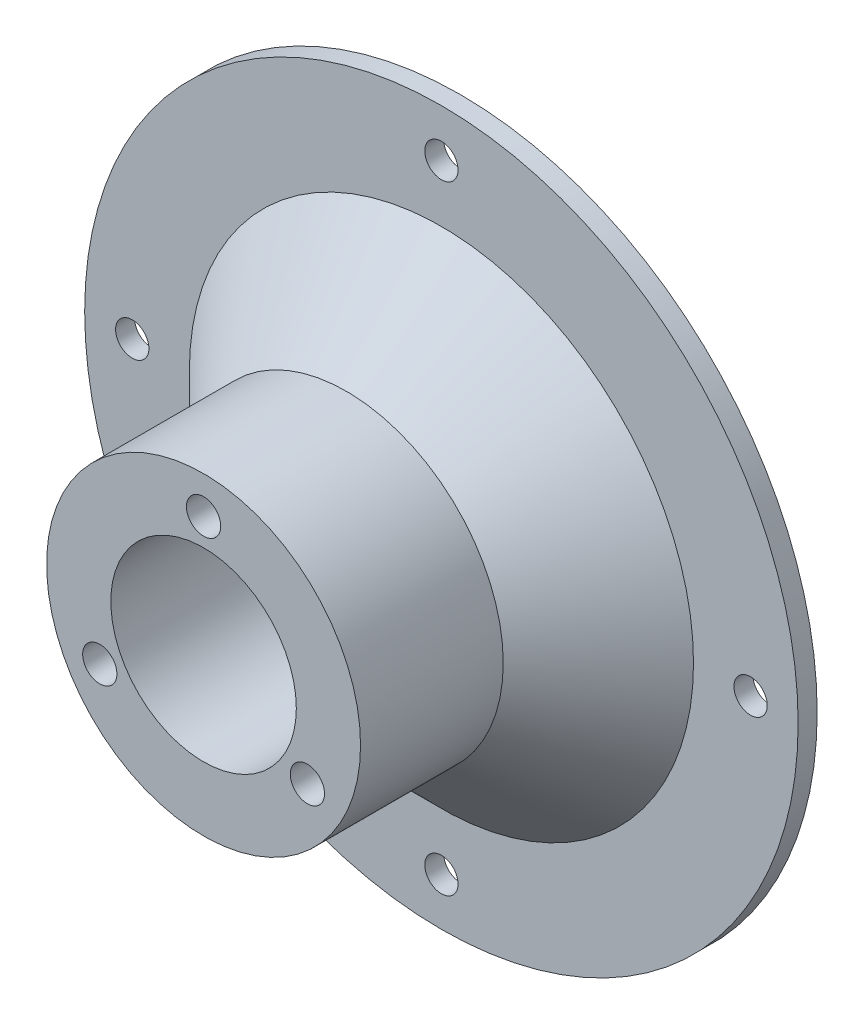
SolidWorks part; units mm, degrees
ref_plane "Спереди" through (0, 0, 0) normal (0, 0, 1) x (1, 0, 0)
ref_plane "Сверху" through (0, 0, 0) normal (0, 1, 0) x (1, 0, 0)
ref_plane "Справа" through (0, 0, 0) normal (1, 0, 0) x (0, 0, -1)
other "Configuration Table"
sketch "Эскиз1" plane through (0, 0, 0) normal (0, 0, 1) x (1, 0, 0)
  circle A0 centre (0, 0) radius 37.5
  dimension "D1" = 75
extrude "Бобышка-Вытянуть1" add sketch "Эскиз1" along normal blind 2
sketch "Эскиз2" plane through (0, 0, 2) normal (0, 0, 1) x (1, 0, 0)
  circle A1 centre (0, 0) radius 32.5 construction
  circle A2 centre (0, 32.5) radius 1.75
  circle A3 centre (32.5, 0) radius 1.75
  circle A4 centre (0, -32.5) radius 1.75
  circle A5 centre (-32.5, 0) radius 1.75
  point P15 (0, 0)
  dimension "D1" = 65
  dimension "D2" = 3.5
  dimension "D3" = 4
extrude "Вырез-Вытянуть1" cut sketch "Эскиз2" against normal up to surface (2 mm away) up to face at (37.5, 0, 0)
sketch "Эскиз3" plane through (0, 0, 2) normal (0, 0, 1) x (1, 0, 0)
  circle A0 centre (0, 0) radius 16.5
  dimension "D1" = 33
extrude "Бобышка-Вытянуть2" add sketch "Эскиз3" along normal blind 25
sketch "Эскиз4" plane through (0, 0, 27) normal (0, 0, 1) x (1, 0, 0)
  circle A0 centre (0, 0) radius 9.75
  circle A1 centre (0, 0) radius 12.6 construction
  circle A2 centre (0, 12.6) radius 1.8
  circle A3 centre (10.9119, -6.3) radius 1.8
  circle A4 centre (-10.9119, -6.3) radius 1.8
  point P12 (0, 0)
  dimension "D1" = 19.5
  dimension "D2" = 3.6
  dimension "D3" = 25.2
  dimension "D4" = 3
extrude "Вырез-Вытянуть2" cut sketch "Эскиз4" against normal up to surface (27 mm away) up to face at (1.75, 32.5, 0)
chamfer "Фаска1" distance 10 angle 45 1 edges at (16.5, 0, 2)
